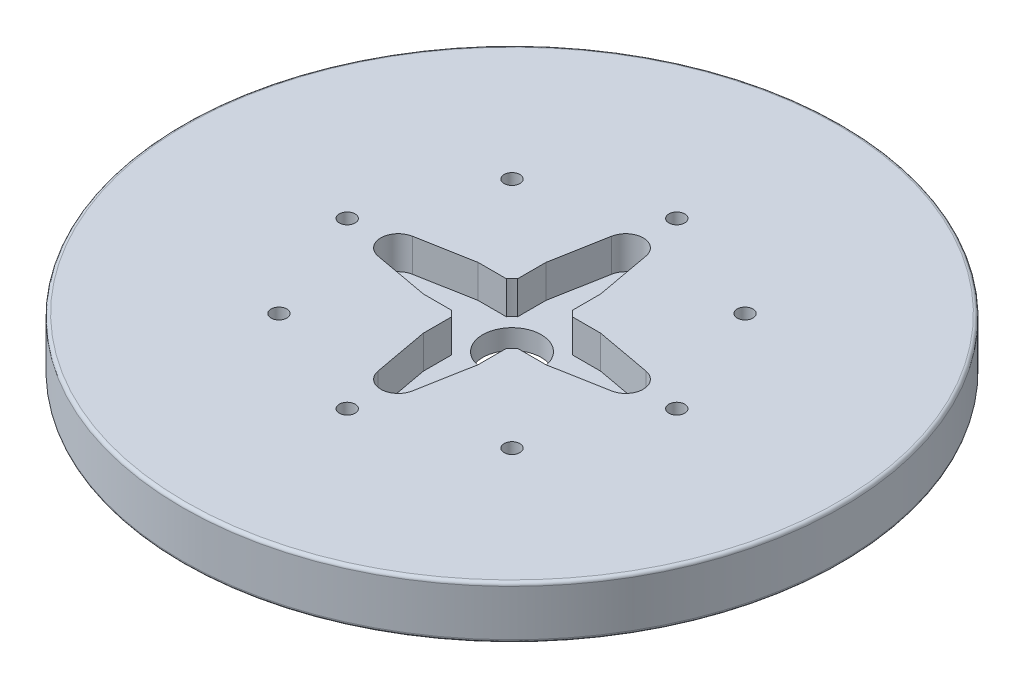
SolidWorks part; units mm, degrees
ref_plane "Front Plane" through (0, 0, 0) normal (0, 0, 1) x (1, 0, 0)
ref_plane "Top Plane" through (0, 0, 0) normal (0, 1, 0) x (1, 0, 0)
ref_plane "Right Plane" through (0, 0, 0) normal (1, 0, 0) x (0, 0, -1)
sketch "Sketch2" plane through (0, 0, 0) normal (0, 1, 0) x (1, 0, 0)
  line L0 (0, 19.5) -> (0, -19.5) construction
  line L1 (-19.9, 0) -> (19.9, 0) construction
  line L2 (9.3027, 4.15) -> (17.7275, 2.6066)
  line L3 (17.7275, -2.6066) -> (9.3027, -4.15)
  line L4 (5.0027, 4.15) -> (9.3027, 4.15)
  line L5 (5.0027, -4.15) -> (9.3027, -4.15)
  line L6 (4.15, -5.0027) -> (4.15, -9.3027)
  line L7 (-2.6066, -17.7275) -> (-4.15, -9.3027)
  line L8 (-4.15, -5.0027) -> (-4.15, -9.3027)
  line L9 (4.15, -9.3027) -> (2.6066, -17.7275)
  line L10 (-5.0027, -4.15) -> (-9.3027, -4.15)
  line L11 (-17.7275, 2.6066) -> (-9.3027, 4.15)
  line L12 (-5.0027, 4.15) -> (-9.3027, 4.15)
  line L13 (-9.3027, -4.15) -> (-17.7275, -2.6066)
  line L14 (-4.15, 5.0027) -> (-4.15, 9.3027)
  line L15 (2.6066, 17.7275) -> (4.15, 9.3027)
  line L16 (4.15, 5.0027) -> (4.15, 9.3027)
  line L17 (-4.15, 9.3027) -> (-2.6066, 17.7275)
  arc A0 (4.15, -5.0027) -> (5.0027, -4.15) centre (0, 0) ccw
  arc A1 (17.7275, -2.6066) -> (17.7275, 2.6066) centre (17.25, 0) ccw
  arc A2 (-2.6066, -17.7275) -> (2.6066, -17.7275) centre (0, -17.25) ccw
  arc A3 (-17.7275, 2.6066) -> (-17.7275, -2.6066) centre (-17.25, 0) ccw
  arc A4 (2.6066, 17.7275) -> (-2.6066, 17.7275) centre (0, 17.25) ccw
  arc A5 (-5.0027, -4.15) -> (-4.15, -5.0027) centre (0, 0) ccw
  arc A6 (-4.15, 5.0027) -> (-5.0027, 4.15) centre (0, 0) ccw
  arc A7 (5.0027, 4.15) -> (4.15, 5.0027) centre (0, 0) ccw
  circle A8 centre (0, 0) radius 50
  circle A12 centre (25, 0) radius 1.2
  circle A13 centre (17.6777, -17.6777) radius 1.2
  circle A14 centre (0, -25) radius 1.2
  circle A15 centre (-17.6777, -17.6777) radius 1.2
  circle A16 centre (-25, 0) radius 1.2
  circle A17 centre (-17.6777, 17.6777) radius 1.2
  circle A18 centre (0, 25) radius 1.2
  circle A19 centre (17.6777, 17.6777) radius 1.2
  point P5 (0, 0)
  point P7 (0, 0)
  point P40 (0, 0)
  dimension "D3" = 12.7248
  dimension "D4" = 5.3
  dimension "D10" = 2.4
  dimension "D8" = 6.5
  dimension "D9" = 100
  dimension "D1" = 8.4248
  dimension "D2" = 39
  dimension "D5" = 4
  dimension "D6" = 4.15
  dimension "D7" = 8.3
  dimension "D11" = 25
  dimension "D12" = 8
extrude "Boss-Extrude1" add sketch "Sketch2" along normal blind 8
sketch "Sketch3" plane through (0, 0, 0) normal (0, -1, 0) x (1, 0, 0)
  circle A0 centre (0, 0) radius 19.9
  arc A1 (-17.7275, 2.6066) -> (-17.7275, -2.6066) centre (-17.25, 0) ccw construction
  circle A2 centre (0, 0) radius 4.45
  dimension "D1" = 8.9
extrude "Boss-Extrude2" add sketch "Sketch3" against normal blind 3
sketch "Sketch4" plane through (0, 0, 0) normal (0, -1, 0) x (1, 0, 0)
  circle A0 centre (0, 25) radius 2.05
  circle A1 centre (0, 25) radius 2.05
  circle A2 centre (0, 25) radius 2.05
  circle A3 centre (0, 25) radius 2.05
  circle A4 centre (0, 25) radius 2.05
  circle A5 centre (0, 25) radius 2.05
  circle A6 centre (0, 25) radius 2.05
  circle A7 centre (0, 25) radius 2.05
  circle A8 centre (17.6777, 17.6777) radius 2.05
  circle A10 centre (25, 0) radius 2.05
  circle A11 centre (17.6777, -17.6777) radius 2.05
  circle A12 centre (0, -25) radius 2.05
  circle A13 centre (-17.6777, -17.6777) radius 2.05
  circle A14 centre (-25, 0) radius 2.05
  circle A15 centre (-17.6777, 17.6777) radius 2.05
  point P34 (0, 0)
  dimension "D1" = 4.1
  dimension "D2" = 8
  dimension "D3" = 8
extrude "Cut-Extrude2" cut sketch "Sketch4" against normal blind 3 contours A15 A5 | A14 A6 | A13 A8 | A12 A10 | A11 | A0 A3 | A8 A2 | A10 A7
fillet "Fillet1" radius 1 8 edges at (0, 0, -27.05) (17.6777, 0, -19.7277) (25, 0, -2.05) (17.6777, 0, 15.6277) (0, 0, 22.95) (-17.6777, 0, 15.6277) (-25, 0, -2.05) (-17.6777, 0, -19.7277)
fillet "Fillet2" radius 0.5 2 edges at (0, 0, 50) (0, 8, 50)
